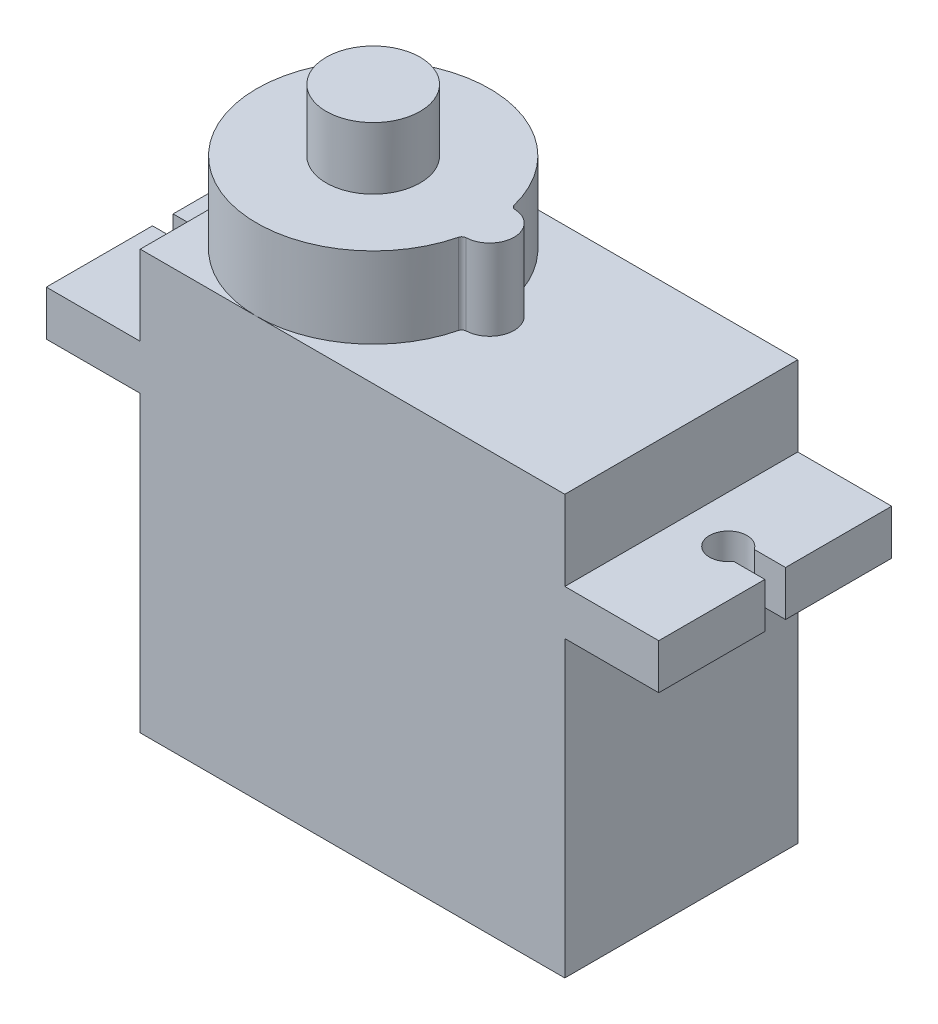
SolidWorks part; units mm, degrees
ref_plane "Front Plane" through (0, 0, 0) normal (0, 0, 1) x (1, 0, 0)
ref_plane "Top Plane" through (0, 0, 0) normal (0, 1, 0) x (1, 0, 0)
ref_plane "Right Plane" through (0, 0, 0) normal (1, 0, 0) x (0, 0, -1)
sketch "Sketch3" plane through (0, 0, 0) normal (0, 1, 0) x (1, 0, 0)
  line L1 (11.3, 6.2) -> (-11.3, 6.2)
  line L2 (11.3, 6.2) -> (11.3, -6.2)
  line L3 (11.3, -6.2) -> (-11.3, -6.2)
  line L4 (-11.3, 6.2) -> (-11.3, -6.2)
  line L5 (11.3, 6.2) -> (-11.3, -6.2) construction
  line L6 (11.3, -6.2) -> (-11.3, 6.2) construction
  point P0 (0, 0)
  dimension "D1" = 22.6
  dimension "D2" = 12.4
extrude "Boss-Extrude1" add sketch "Sketch3" along normal blind 22.3
sketch "Sketch4" plane through (0, 0, 6.2) normal (0, 0, 1) x (1, 0, 0)
  line L0 (11.3, 22.3) -> (11.3, 0) construction
  line L1 (11.3, 18.05) -> (16.3, 18.05)
  line L2 (11.3, 18.05) -> (11.3, 15.65)
  line L3 (11.3, 15.65) -> (16.3, 15.65)
  line L4 (16.3, 18.05) -> (16.3, 15.65)
  line L5 (-11.3, 22.3) -> (11.3, 22.3) construction
  line L6 (0, 0) -> (0, 13.9537) construction
  line L7 (-16.3, 18.05) -> (-16.3, 15.65)
  line L8 (-11.3, 15.65) -> (-16.3, 15.65)
  line L9 (-11.3, 18.05) -> (-11.3, 15.65)
  line L10 (-11.3, 18.05) -> (-16.3, 18.05)
  dimension "D1" = 4.25
  dimension "D2" = 2.4
  dimension "D3" = 5
extrude "Boss-Extrude2" add sketch "Sketch4" against normal up to vertex (12.4 mm away)
sketch "Sketch5" plane through (0, 18.05, 0) normal (0, 1, 0) x (1, 0, 0)
  line L0 (13.8, 0) -> (0, 0) construction
  line L1 (14.6352, 0.55) -> (16.3, 0.55)
  line L2 (16.3, 6.2) -> (16.3, -6.2) construction
  line L3 (16.3, 0.55) -> (16.3, -0.55)
  line L4 (16.3, -0.55) -> (14.6352, -0.55)
  arc A0 (14.6352, 0.55) -> (14.6352, -0.55) centre (13.8, 0) ccw
  dimension "D1" = 1.1
  dimension "D2" = 2
  dimension "D3" = 2.5
extrude "Cut-Extrude1" cut sketch "Sketch5" against normal blind 22.3
mirror "Mirror1" about plane through (0, 0, 0) normal (1, 0, 0) of "Cut-Extrude1"
sketch "Sketch7" plane through (0, 22.3, 0) normal (0, 1, 0) x (1, 0, 0)
  line L0 (-11.3, 6.2) -> (-11.3, -6.2) construction
  arc A0 (0.9186, 1.4888) -> (0.9186, -1.4888) centre (-5.1, 0) ccw
  arc A1 (1.1514, -1.299) -> (1.1514, 1.299) centre (1.1, 0) ccw
  arc A2 (1.1514, 1.299) -> (0.9186, 1.4888) centre (1.1613, 1.5488) cw
  arc A3 (1.1514, -1.299) -> (0.9186, -1.4888) centre (1.1613, -1.5488) ccw
  point P1 (0, 0)
  dimension "D1" = 12.4
  dimension "D2" = 2.6
  dimension "D3" = 0.25
extrude "Boss-Extrude3" add sketch "Sketch7" along normal blind 4.3
sketch "Sketch8" plane through (0, 26.6, 0) normal (0, 1, 0) x (1, 0, 0)
  circle A0 centre (-5.1, 0) radius 2.5
  dimension "D1" = 5
extrude "Boss-Extrude4" add sketch "Sketch8" along normal blind 3.3
sketch "Sketch9" plane through (-11.3, 0, 0) normal (-1, 0, 0) x (0, 0, 1)
  circle A0 centre (0, 4.5) radius 0.6
  circle A1 centre (1.2, 4.5) radius 0.6
  circle A2 centre (-1.2, 4.5) radius 0.6
  point P6 (0, 0)
  point P8 (0, 0)
  dimension "D1" = 1.2
  dimension "D2" = 4.5
extrude "Boss-Extrude6" add sketch "Sketch9" along normal blind 3.3 separate body contours A2 | A0 | A1
